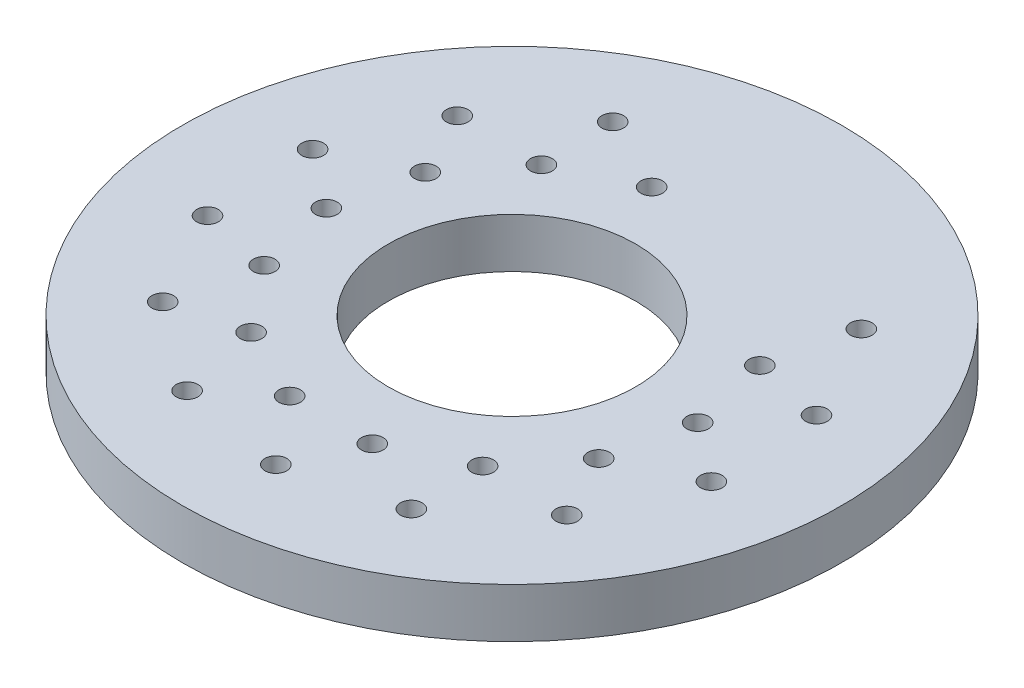
SolidWorks part; units mm, degrees
ref_plane "Front Plane" through (0, 0, 0) normal (0, 0, 1) x (1, 0, 0)
ref_plane "Top Plane" through (0, 0, 0) normal (0, 1, 0) x (1, 0, 0)
ref_plane "Right Plane" through (0, 0, 0) normal (1, 0, 0) x (0, 0, -1)
sketch "Sketch1" plane through (0, 0, 0) normal (0, 1, 0) x (1, 0, 0)
  circle A0 centre (-21.7363, 18.9571) radius 10.65
extrude "Boss-Extrude1" add sketch "Sketch1" along normal blind 1.6
sketch "Sketch2" plane through (0, 1.6, 0) normal (0, 1, 0) x (1, 0, 0)
  line L1 (-21.7363, 29.6071) -> (-21.7363, 8.3071) construction
  line L2 (-21.7363, 18.9571) -> (-27.7363, 18.9571) construction
  circle A0 centre (-27.1421, 21.5604) radius 0.35
  circle A1 centre (-25.4773, 23.6481) radius 0.35
  circle A2 centre (-23.0714, 24.8067) radius 0.35
  circle A5 centre (-16.3305, 21.5604) radius 0.35
  circle A6 centre (-15.7363, 18.9571) radius 0.35
  circle A7 centre (-16.3305, 16.3538) radius 0.35
  circle A8 centre (-17.9954, 14.2661) radius 0.35
  circle A9 centre (-20.4012, 13.1075) radius 0.35
  circle A10 centre (-23.0714, 13.1075) radius 0.35
  circle A11 centre (-25.4773, 14.2661) radius 0.35
  circle A12 centre (-27.1421, 16.3538) radius 0.35
  circle A14 centre (-21.7363, 18.9571) radius 10.65 construction
  circle A15 centre (-27.7363, 18.9571) radius 0.35
  circle A16 centre (-20.4012, 24.8067) radius 0.35 [skipped]
  circle A17 centre (-17.9954, 23.6481) radius 0.35 [skipped]
  dimension "D2" = 14
  dimension "D1" = 6
extrude "Cut-Extrude1" cut sketch "Sketch2" against normal through all
sketch "Sketch3" plane through (0, 1.6, 0) normal (0, 1, 0) x (1, 0, 0)
  line L0 (-21.7363, 29.6071) -> (-21.7363, 8.3071) construction
  line L1 (-32.3863, 18.9571) -> (-11.0863, 18.9571) construction
  circle A0 centre (-21.7363, 18.9571) radius 10.65 construction
  circle A1 centre (-21.7363, 18.9571) radius 4
  dimension "D1" = 8
extrude "Cut-Extrude2" cut sketch "Sketch3" against normal through all
sketch "Sketch7" plane through (0, 1.6, 0) normal (0, 1, 0) x (1, 0, 0)
  line L2 (-24.8805, 11.6009) -> (-21.7363, 18.9571) construction
  circle A0 centre (-27.7609, 13.6936) radius 0.35
  circle A1 centre (-29.448, 16.8288) radius 0.35
  circle A2 centre (-29.6078, 20.3856) radius 0.35
  circle A3 centre (-28.2085, 23.6594) radius 0.35
  circle A4 centre (-25.5273, 26.0019) radius 0.35
  circle A7 centre (-15.7117, 24.2206) radius 0.35
  circle A8 centre (-14.0246, 21.0854) radius 0.35
  circle A9 centre (-24.8805, 11.6009) radius 0.35
  circle A10 centre (-13.8649, 17.5287) radius 0.35
  circle A11 centre (-15.2642, 14.2548) radius 0.35
  circle A12 centre (-17.9454, 11.9123) radius 0.35
  circle A13 centre (-21.3774, 10.9652) radius 0.35
  circle A30 centre (-18.5921, 26.3133) radius 0.35 [skipped]
  circle A31 centre (-22.0952, 26.9491) radius 0.35 [skipped]
  dimension "D1" = 14
extrude "Cut-Extrude6" cut sketch "Sketch7" against normal blind 10
